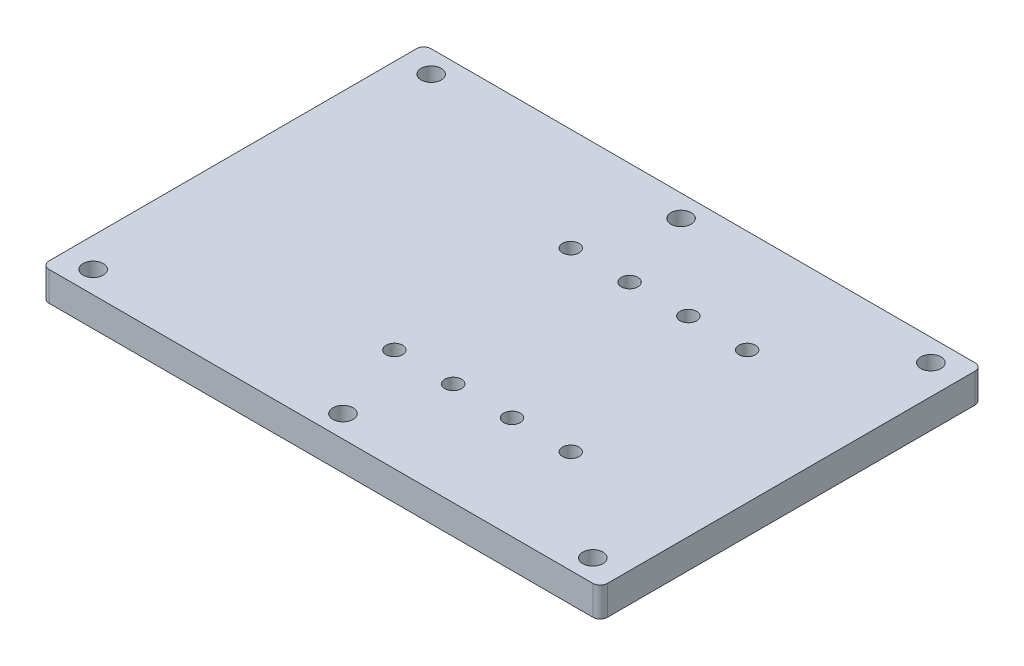
SolidWorks part; units mm, degrees
material "Balsa"
ref_plane "Front Plane" through (0, 0, 0) normal (0, 0, 1) x (1, 0, 0)
ref_plane "Top Plane" through (0, 0, 0) normal (0, 1, 0) x (1, 0, 0)
ref_plane "Right Plane" through (0, 0, 0) normal (1, 0, 0) x (0, 0, -1)
sketch "Sketch1" plane through (0, 0, 0) normal (0, 1, 0) x (1, 0, 0)
  line L1 (-241.3, 165.1) -> (241.3, 165.1)
  line L2 (-241.3, 165.1) -> (-241.3, -165.1)
  line L3 (-241.3, -165.1) -> (241.3, -165.1)
  line L4 (241.3, 165.1) -> (241.3, -165.1)
  line L5 (-241.3, 165.1) -> (241.3, -165.1) construction
  line L6 (-241.3, -165.1) -> (241.3, 165.1) construction
  point P0 (0, 0)
  dimension "D1" = 330.2
  dimension "D2" = 482.6
extrude "Boss-Extrude1" add sketch "Sketch1" along normal blind 25.4
sketch "Sketch2" plane through (0, 25.4, 0) normal (0, 1, 0) x (1, 0, 0)
  line L0 (241.3, -165.1) -> (241.3, 165.1) construction
  line L1 (-215.9, 146.05) -> (215.9, 146.05) construction
  line L2 (-215.9, 146.05) -> (-215.9, -146.05) construction
  line L3 (-215.9, -146.05) -> (215.9, -146.05) construction
  line L4 (215.9, 146.05) -> (215.9, -146.05) construction
  line L5 (-215.9, 146.05) -> (215.9, -146.05) construction
  line L6 (-215.9, -146.05) -> (215.9, 146.05) construction
  line L7 (-241.3, -165.1) -> (241.3, -165.1) construction
  line L8 (0, 146.05) -> (0, -146.05) construction
  circle A0 centre (215.9, 146.05) radius 8.7376
  circle A1 centre (-215.9, 146.05) radius 8.7376
  circle A2 centre (215.9, -146.05) radius 8.7376
  circle A3 centre (-215.9, -146.05) radius 8.7376
  circle A4 centre (0, 146.05) radius 8.7376
  circle A5 centre (0, -146.05) radius 8.7376
  point P0 (0, 0)
  dimension "D1" = 17.4752
  dimension "D2" = 25.4
  dimension "D3" = 19.05
extrude "Cut-Extrude1" cut sketch "Sketch2" against normal through all both and the other way through all
sketch "Sketch4" plane through (0, 25.4, 0) normal (0, 1, 0) x (1, 0, 0)
  line L0 (-1000, 0) -> (49000, 0) construction
  line L1 (-25.4, 76.2) -> (25.4, 76.2) construction
  line L2 (25.4, 76.2) -> (76.2, 76.2) construction
  line L3 (76.2, 76.2) -> (127, 76.2) construction
  line L5 (-241.3, 165.1) -> (-241.3, -165.1) construction
  line L6 (76.2, -76.2) -> (127, -76.2) construction
  line L7 (25.4, -76.2) -> (76.2, -76.2) construction
  line L8 (-25.4, -76.2) -> (25.4, -76.2) construction
  circle A0 centre (-25.4, 76.2) radius 7.1628
  circle A1 centre (25.4, 76.2) radius 7.1628
  circle A2 centre (76.2, 76.2) radius 7.1628
  circle A3 centre (127, 76.2) radius 7.1628
  circle A4 centre (127, -76.2) radius 7.1628
  circle A5 centre (76.2, -76.2) radius 7.1628
  circle A6 centre (25.4, -76.2) radius 7.1628
  circle A7 centre (-25.4, -76.2) radius 7.1628
  dimension "D3" = 14.3256
  dimension "D1" = 50.8
  dimension "D2" = 76.2
  dimension "D4" = 215.9
extrude "Cut-Extrude2" cut sketch "Sketch4" against normal through all both and the other way through all
fillet "Fillet1" radius 6.35 4 edges at (-241.3, 12.7, 165.1) (241.3, 12.7, 165.1) (241.3, 12.7, -165.1) (-241.3, 12.7, -165.1)
